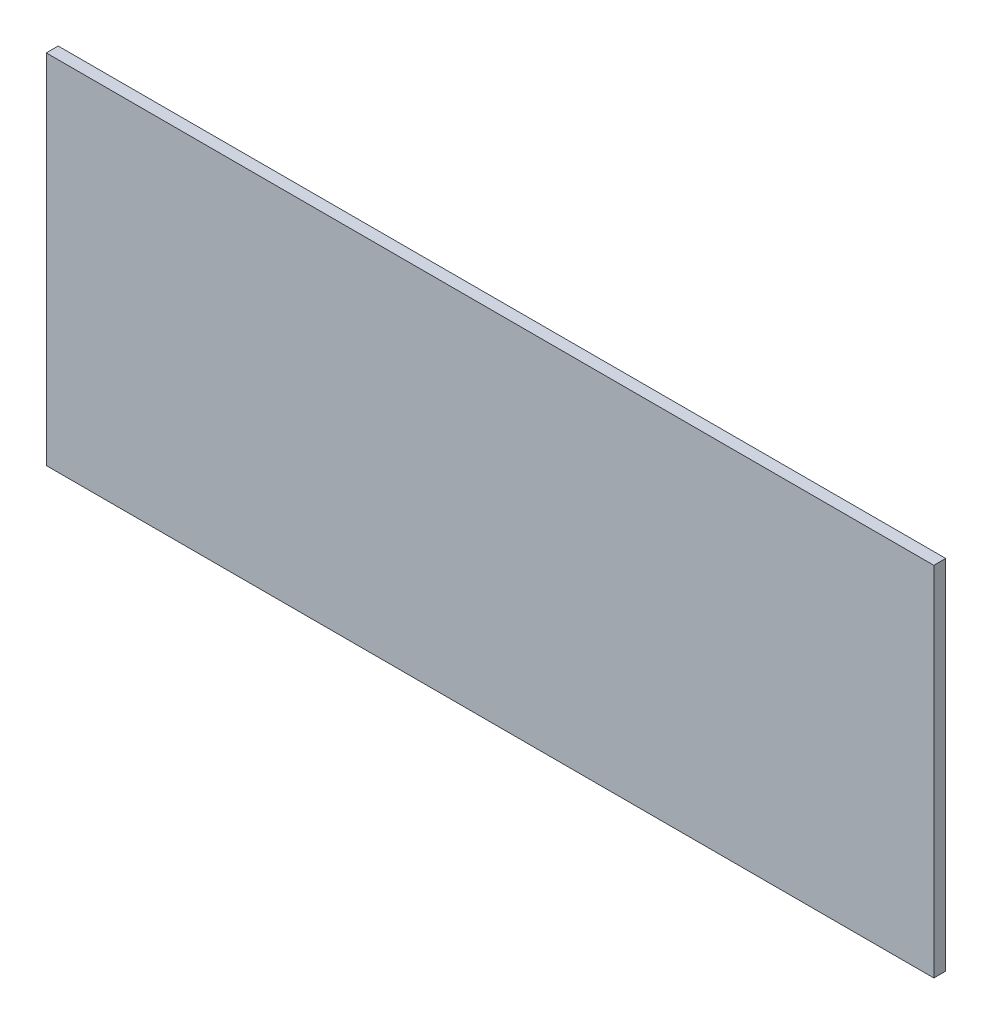
SolidWorks part; units mm, degrees
ref_plane "Front Plane" through (0, 0, 0) normal (0, 0, 1) x (1, 0, 0)
ref_plane "Top Plane" through (0, 0, 0) normal (0, 1, 0) x (1, 0, 0)
ref_plane "Right Plane" through (0, 0, 0) normal (1, 0, 0) x (0, 0, -1)
sketch "Sketch1" plane through (0, 0, 0) normal (0, 0, 1) x (1, 0, 0)
  line L1 (-74.5, -30) -> (74.5, -30)
  line L2 (-74.5, -30) -> (-74.5, 30)
  line L3 (-74.5, 30) -> (74.5, 30)
  line L4 (74.5, -30) -> (74.5, 30)
  line L5 (-74.5, -30) -> (74.5, 30) construction
  line L6 (-74.5, 30) -> (74.5, -30) construction
  point P0 (0, 0)
  dimension "D1" = 60
  dimension "D2" = 149
extrude "Boss-Extrude1" add sketch "Sketch1" along normal blind 2
